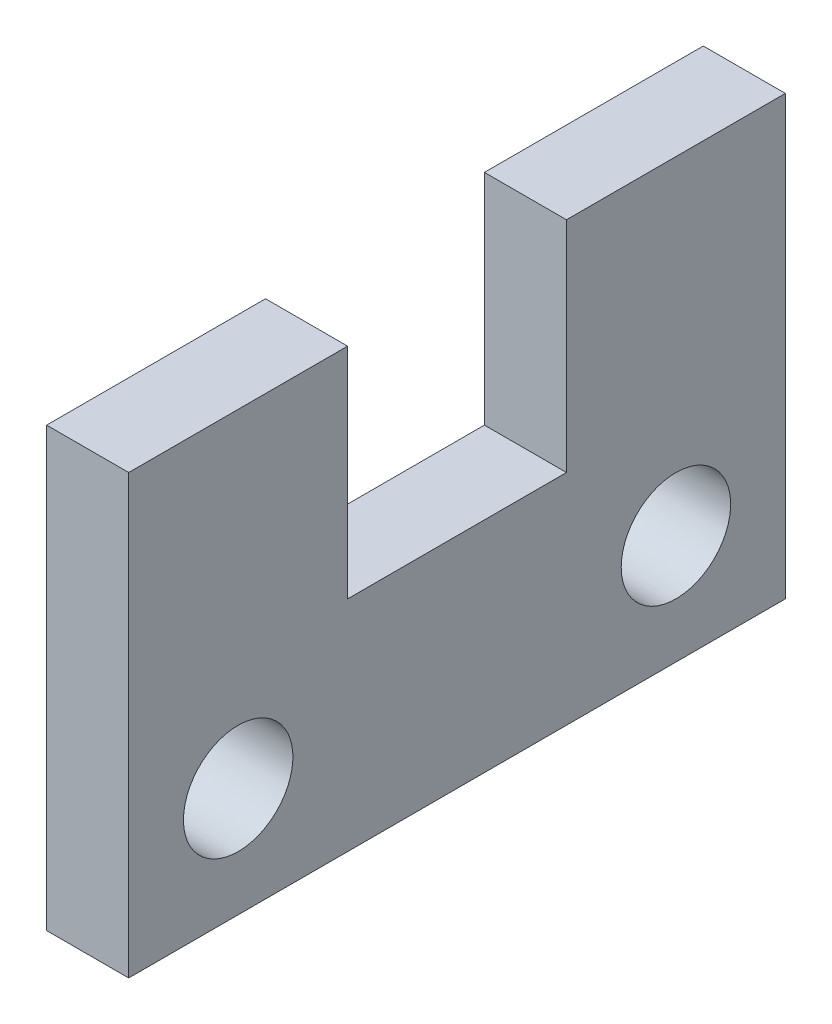
SolidWorks part; units mm, degrees
ref_plane "Front Plane" through (0, 0, 0) normal (0, 0, 1) x (1, 0, 0)
ref_plane "Top Plane" through (0, 0, 0) normal (0, 1, 0) x (1, 0, 0)
ref_plane "Right Plane" through (0, 0, 0) normal (1, 0, 0) x (0, 0, -1)
sketch "Sketch1" plane through (0, 0, 0) normal (0, 1, 0) x (1, 0, 0)
  line L0 (0, 0) -> (88.9, 0)
  dimension "D1" = 88.9
sketch "Sketch2" plane through (0, 0, 0) normal (0, 1, 0) x (1, 0, 0)
  line L0 (-10, 5) -> (10, 5)
  point P0 (10, 5)
  point P3 (0, 5)
  dimension "D1" = 20
  dimension "D2" = 5
sketch "Sketch3" plane through (0, 0, 0) normal (1, 0, 0) x (0, 0, -1)
  line L0 (0, 0) -> (120, 0)
  line L1 (120, 0) -> (120, 80)
  line L2 (120, 80) -> (80, 80)
  line L3 (80, 80) -> (80, 40)
  line L4 (80, 40) -> (40, 40)
  line L5 (40, 40) -> (40, 80)
  line L6 (40, 80) -> (0, 80)
  line L7 (0, 80) -> (0, 0)
  dimension "D1" = 120
  dimension "D2" = 80
  dimension "D3" = 40
  dimension "D4" = 40
  dimension "D5" = 40
extrude "Boss-Extrude1" add sketch "Sketch3" along normal blind 15
sketch "Sketch5" plane through (0, 0, 0) normal (-1, 0, 0) x (0, 0, 1)
  line L0 (-120, 20) -> (0, 20) construction
  line L1 (-120, 0) -> (-120, 80) construction
  line L2 (0, 80) -> (0, 0) construction
  line L3 (-100, 80) -> (-100, 0) construction
  line L4 (-120, 80) -> (-80, 80) construction
  line L5 (0, 0) -> (-120, 0) construction
  line L6 (-20, 80) -> (-20, 0) construction
  line L7 (-40, 80) -> (0, 80) construction
  circle A0 centre (-100, 20) radius 10
  circle A1 centre (-20, 20) radius 10
  dimension "D4" = 20
  dimension "D5" = 20
  dimension "D1" = 20
  dimension "D2" = 20
  dimension "D3" = 20
extrude "Cut-Extrude1" cut sketch "Sketch5" against normal blind 15
